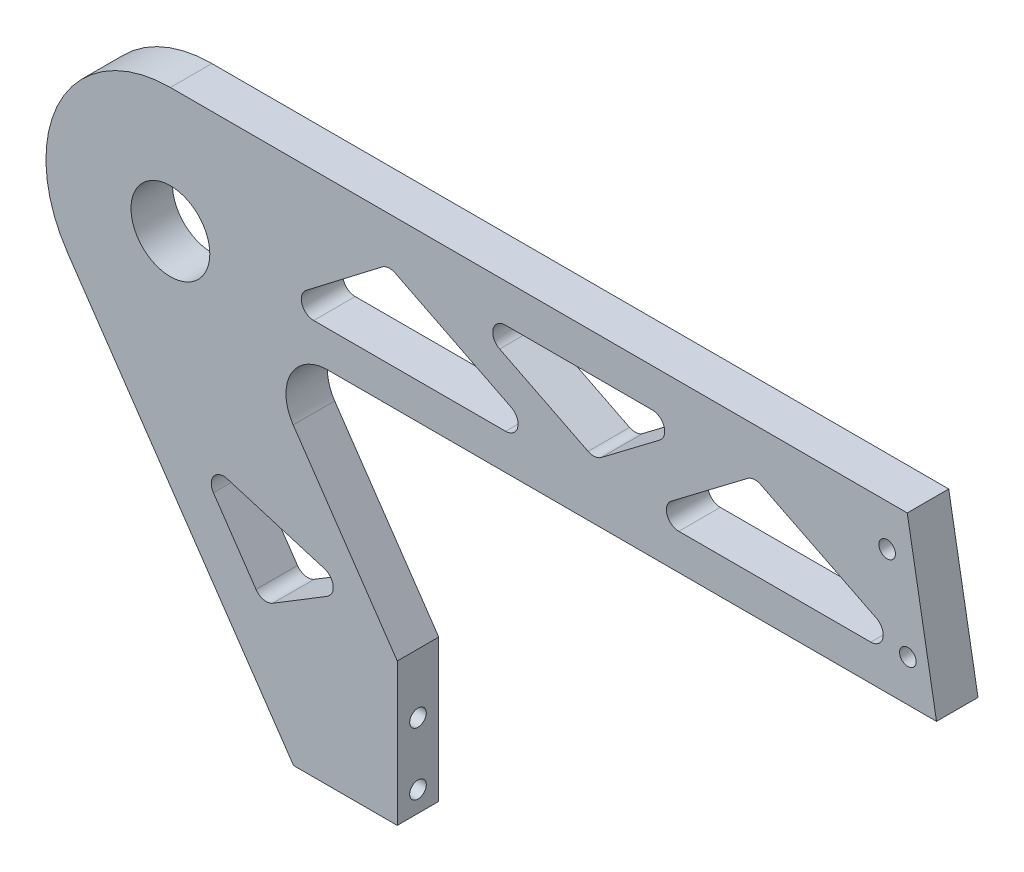
SolidWorks part; units mm, degrees
ref_plane "Front Plane" through (0, 0, 0) normal (0, 0, 1) x (1, 0, 0)
ref_plane "Top Plane" through (0, 0, 0) normal (0, 1, 0) x (1, 0, 0)
ref_plane "Right Plane" through (0, 0, 0) normal (1, 0, 0) x (0, 0, -1)
sketch "Sketch1" plane through (0, 0, 0) normal (0, 0, 1) x (1, 0, 0)
  line L0 (0, 0) -> (-25, 0)
  line L1 (-25, 0) -> (-79.4657, 79.8008)
  line L2 (-54.687, 126.7128) -> (122.9469, 126.7128)
  line L3 (122.9469, 126.7128) -> (130, 86.7128)
  line L4 (130, 86.7128) -> (-16.8223, 86.7128)
  line L5 (-25.0818, 71.0755) -> (0, 34.3267)
  line L6 (0, 34.3267) -> (0, 0)
  line L7 (0, 30) -> (150, 30) construction
  line L8 (150, 30) -> (150, -13.554) construction
  line L9 (140, 14.2228) -> (140, 30) construction
  line L10 (140, 30) -> (116.1596, 165.2058) construction
  line L17 (87.6026, 114.9555) -> (115.4893, 101.0273)
  line L18 (114.1489, 95.3435) -> (67.8789, 95.3435)
  line L19 (66.0673, 100.7346) -> (84.4504, 114.6628)
  line L20 (-0.4911, 115.0579) -> (27.4755, 101.0248)
  line L21 (26.1301, 95.3435) -> (-20.1398, 95.3435)
  line L22 (-21.9652, 100.7242) -> (-3.6619, 114.7573)
  line L26 (26.031, 117.4787) -> (61.4709, 117.4787)
  line L27 (63.2826, 112.0875) -> (49.1628, 101.3896)
  line L28 (46.0057, 101.0994) -> (24.6856, 111.7973)
  line L29 (-44.3201, 47.3006) -> (-34.0482, 32.2506)
  line L30 (-30.0093, 31.3799) -> (-16.8655, 39.389)
  line L31 (-17.5627, 44.8238) -> (-40.9784, 51.8647)
  arc A0 (-79.4657, 79.8008) -> (-54.687, 126.7128) centre (-54.687, 96.7128) cw
  arc A1 (-16.8223, 86.7128) -> (-25.0818, 71.0755) centre (-16.8223, 76.7128) ccw
  circle A2 centre (-54.687, 96.7128) radius 9.5
  arc A9 (115.4893, 101.0273) -> (114.1489, 95.3435) centre (114.1489, 98.3435) cw
  arc A10 (67.8789, 95.3435) -> (66.0673, 100.7346) centre (67.8789, 98.3435) cw
  arc A11 (87.6026, 114.9555) -> (84.4504, 114.6628) centre (86.2621, 112.2716) ccw
  arc A12 (27.4755, 101.0248) -> (26.1301, 95.3435) centre (26.1301, 98.3435) cw
  arc A13 (-20.1398, 95.3435) -> (-21.9652, 100.7242) centre (-20.1398, 98.3435) cw
  arc A14 (-0.4911, 115.0579) -> (-3.6619, 114.7573) centre (-1.8366, 112.3765) ccw
  arc A18 (49.1628, 101.3896) -> (46.0057, 101.0994) centre (47.3511, 103.7808) cw
  arc A19 (61.4709, 117.4787) -> (63.2826, 112.0875) centre (61.4709, 114.4787) cw
  arc A20 (26.031, 117.4787) -> (24.6856, 111.7973) centre (26.031, 114.4787) ccw
  arc A21 (-34.0482, 32.2506) -> (-30.0093, 31.3799) centre (-31.5703, 33.9418) ccw
  arc A22 (-16.8655, 39.389) -> (-17.5627, 44.8238) centre (-18.4265, 41.9508) ccw
  arc A23 (-44.3201, 47.3006) -> (-40.9784, 51.8647) centre (-41.8423, 48.9918) cw
  circle A24 centre (118.0922, 116.7128) radius 2
  circle A25 centre (123.0922, 96.7128) radius 2
  dimension "D10" = 30
  dimension "D11" = 10
  dimension "D12" = 19
  dimension "D13" = 3
  dimension "D14" = 3
  dimension "D15" = 4
  dimension "D16" = 4
  dimension "D2" = 40
  dimension "D3" = 40
  dimension "D4" = 30
  dimension "D5" = 25
  dimension "D6" = 150
  dimension "D7" = 10
  dimension "D8" = 130
  dimension "D9" = 80
  dimension "D17" = 10
  dimension "D18" = 10
  dimension "D19" = 5
extrude "Boss-Extrude2" add sketch "Sketch1" along normal mid plane 10 contours L20 A14 L22 A13 L21 A1 L4 A12 | L17 A11 L19 A10 L4 A9 | A24 | A25
sketch "Sketch2" plane through (0, 0, 0) normal (1, 0, 0) x (0, 0, -1)
  circle A0 centre (0, 5) radius 2
  circle A1 centre (0, 20) radius 2
  dimension "D1" = 4
  dimension "D2" = 4
  dimension "D3" = 5
  dimension "D4" = 15
extrude "Cut-Extrude1" cut sketch "Sketch2" against normal mid plane 87
